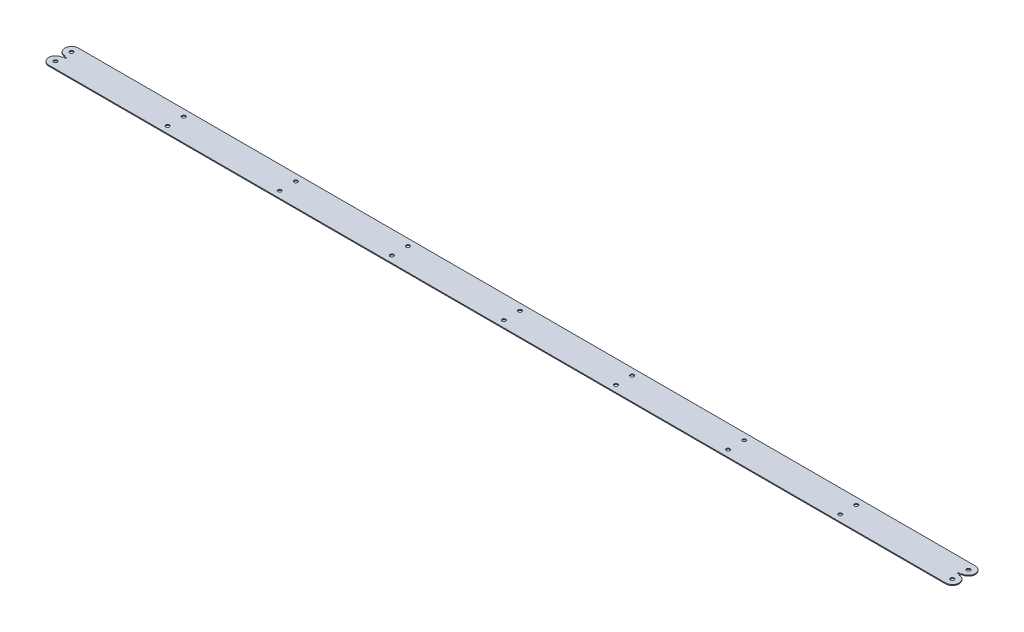
SolidWorks part; units mm, degrees
ref_plane "Front Plane" through (0, 0, 0) normal (0, 0, 1) x (1, 0, 0)
ref_plane "Top Plane" through (0, 0, 0) normal (0, 1, 0) x (1, 0, 0)
ref_plane "Right Plane" through (0, 0, 0) normal (1, 0, 0) x (0, 0, -1)
sketch "Sketch1" plane through (0, 0, 0) normal (0, 1, 0) x (1, 0, 0)
  line L0 (-500, 0) -> (500, 0) construction
  line L5 (-500, 7.5) -> (500, 7.5) construction
  line L6 (-500, 7.5) -> (-500, -7.5) construction
  line L19 (-500, -7.5) -> (500, -7.5)
  line L25 (500, 7.5) -> (500, -7.5) construction
  line L53 (-500, 7.5) -> (500, -7.5) construction
  line L95 (-500, -7.5) -> (500, 7.5) construction
  line L197 (-507.433, -1) -> (-507.5, -1)
  line L198 (-507.5, -1) -> (-507.5, 1)
  line L200 (-507.5, 1) -> (-507.433, 1)
  line L201 (-500, 7.5) -> (-500, 10.5) construction
  line L202 (0, 0) -> (0, 18) construction
  line L203 (500, 7.5) -> (500, 10.5) construction
  line L204 (500, 25.5) -> (-500, 25.5)
  line L205 (500, 25.5) -> (500, 10.5) construction
  line L206 (500, 10.5) -> (-500, 10.5) construction
  line L207 (-500, 25.5) -> (-500, 10.5) construction
  line L208 (500, 25.5) -> (-500, 10.5) construction
  line L209 (500, 10.5) -> (-500, 25.5) construction
  line L210 (-497, 8.5) -> (-497, 9.5)
  line L211 (500, 18) -> (-500, 18) construction
  line L212 (-500, 7.5) -> (-500, 8.5)
  line L213 (-500, 8.5) -> (-497, 8.5)
  line L214 (-497, 9.5) -> (-500, 9.5)
  line L215 (-500, 9.5) -> (-500, 10.5)
  line L216 (500, 10.5) -> (500, 9.5)
  line L217 (500, 9.5) -> (497, 9.5)
  line L218 (497, 9.5) -> (497, 8.5)
  line L219 (497, 8.5) -> (500, 8.5)
  line L220 (500, 8.5) -> (500, 7.5)
  line L221 (500, 9) -> (497, 9) construction
  line L222 (497, 9) -> (-497, 9) construction
  line L223 (-497, 9) -> (-500, 9) construction
  circle A70 centre (0, 0) radius 2
  arc A71 (-500, 7.5) -> (-500, -7.5) centre (-500, 0) ccw construction
  arc A72 (500, -7.5) -> (500, 7.5) centre (500, 0) ccw construction
  circle A73 centre (125, 0) radius 2
  circle A74 centre (250, 0) radius 2
  circle A75 centre (375, 0) radius 2
  circle A76 centre (500, 0) radius 2
  circle A77 centre (-125, 0) radius 2
  circle A78 centre (-250, 0) radius 2
  circle A79 centre (-375, 0) radius 2
  circle A80 centre (-500, 0) radius 2
  arc A81 (-500, 25.5) -> (-500, 10.5) centre (-500, 18) ccw
  arc A82 (500, 10.5) -> (500, 25.5) centre (500, 18) ccw
  arc A83 (500, -7.5) -> (500, 7.5) centre (500, 0) ccw
  arc A84 (-500, -7.5) -> (-507.433, -1) centre (-500, 0) cw
  arc A85 (-507.433, 1) -> (-500, 7.5) centre (-500, 0) cw
  circle A86 centre (0, 18) radius 2
  circle A87 centre (125, 18) radius 2
  circle A88 centre (250, 18) radius 2
  circle A89 centre (375, 18) radius 2
  circle A90 centre (500, 18) radius 2
  circle A91 centre (-125, 18) radius 2
  circle A92 centre (-250, 18) radius 2
  circle A93 centre (-375, 18) radius 2
  circle A94 centre (-500, 18) radius 2
  point P29 (-507.5, 0)
  dimension "D1" = 1000
  dimension "D3" = 4
  dimension "D7" = 5
  dimension "D9" = 1
  dimension "D2" = 5
  dimension "D5" = 2
  dimension "D6" = 15
  dimension "D10" = 3
  dimension "D13" = 125
  dimension "D14" = 125
  dimension "D15" = 33
  dimension "D8" = 5
  dimension "D11" = 3
  dimension "D12" = 125
extrude "Boss-Extrude1" add sketch "Sketch1" along normal blind 1
pattern_linear "LPattern2" [suppressed] count 4 spacing 35
